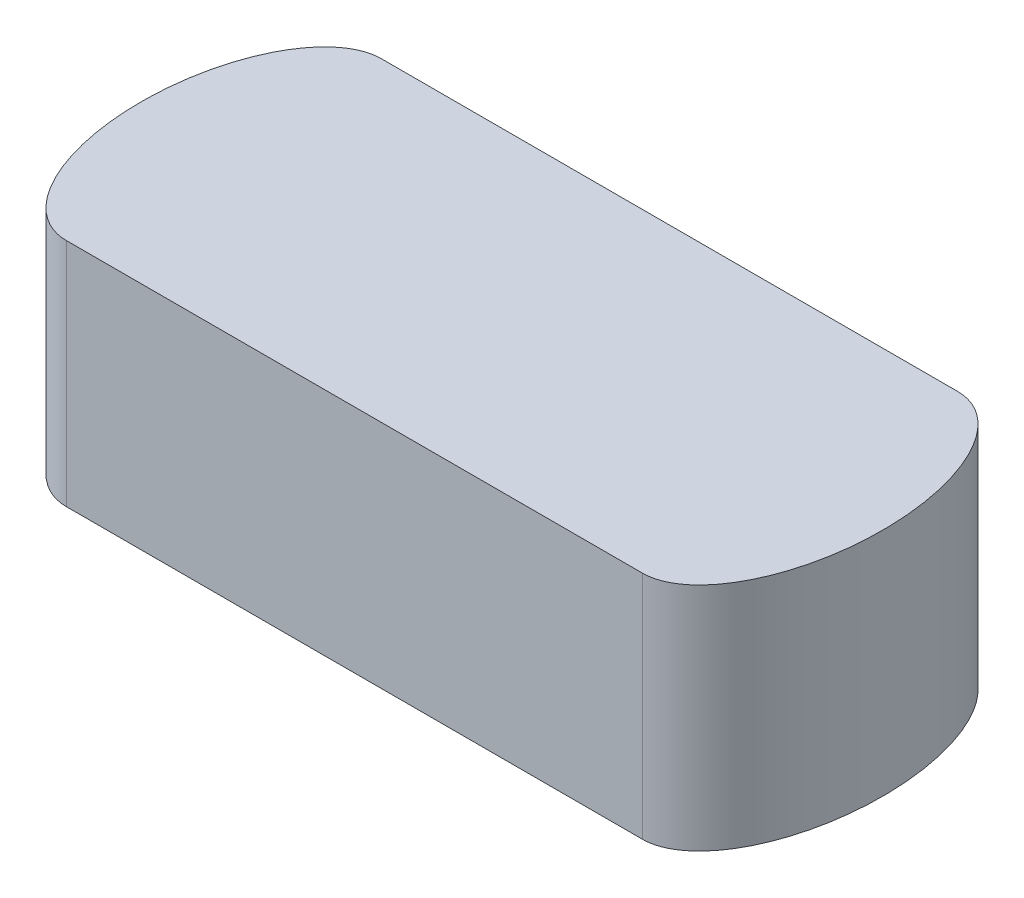
SolidWorks part; units mm, degrees
ref_plane "Front Plane" through (0, 0, 0) normal (0, 0, 1) x (1, 0, 0)
ref_plane "Top Plane" through (0, 0, 0) normal (0, 1, 0) x (1, 0, 0)
ref_plane "Right Plane" through (0, 0, 0) normal (1, 0, 0) x (0, 0, -1)
sketch "Sketch1" plane through (0, 0, 0) normal (0, 1, 0) x (1, 0, 0)
  line L1 (-250, 136.6559) -> (0, 136.6559)
  line L3 (-250, -136.6559) -> (0, -136.6559)
  line L4 (0, 136.6559) -> (0, -136.6559)
  ellipse E0 centre (-250, 0) end of major axis (-250, -136.6559) minor radius 71.8596 (-250, 136.6559) -> (-250, -136.6559) ccw
  point P0 (0, 0)
  dimension "D1" = 250
  dimension "D2" = 273.3119
extrude "Boss-Extrude1" add sketch "Sketch1" along normal blind 200
mirror "Mirror1" about plane through (0, 200, -136.6559) normal (-1, 0, 0) of "Boss-Extrude1"
